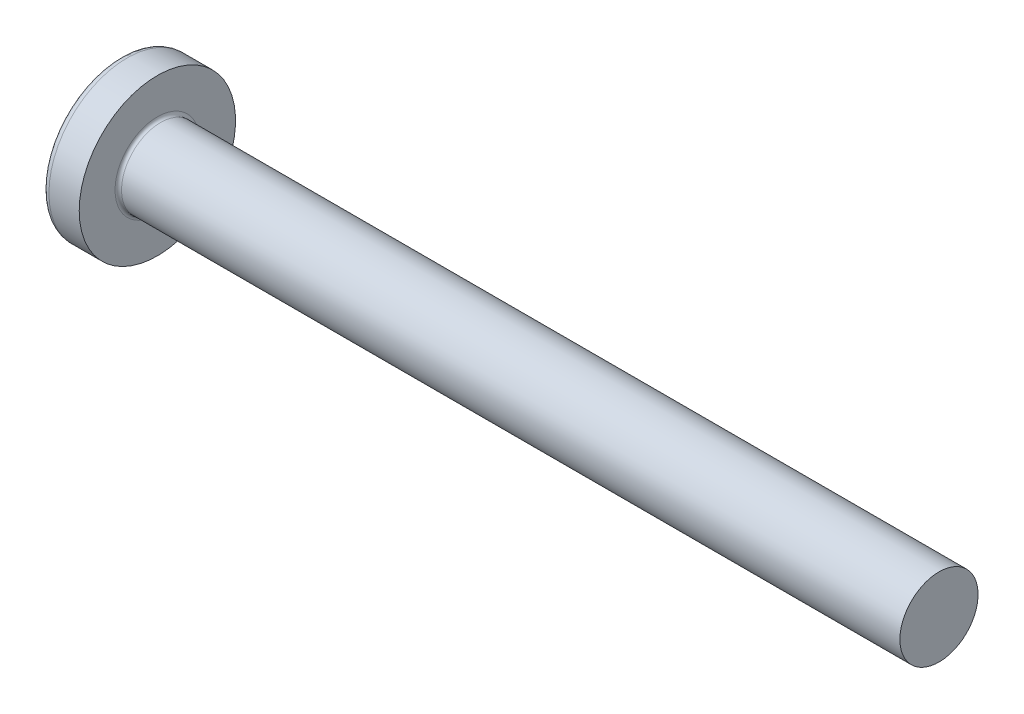
SolidWorks part; units mm, degrees
ref_plane "Plane1" through (0, 0, 0) normal (0, 0, 1) x (1, 0, 0)
ref_plane "Plane2" through (0, 0, 0) normal (0, 1, 0) x (1, 0, 0)
ref_plane "Plane3" through (0, 0, 0) normal (1, 0, 0) x (0, 0, -1)
sketch "BodySke" plane through (0, 0, 0) normal (0, 0, 1) x (1, 0, 0)
  line L0 (4.6, 3) -> (4.6, 6)
  line L1 (5.1, 6.35) -> (5.1, -3.175) construction
  line L2 (-25.4, 0) -> (127, 0) construction
  line L3 (64.6, 0) -> (0, 0)
  line L4 (4.6, 3) -> (64.6, 3)
  line L5 (64.6, 3) -> (64.6, 0)
  line L6 (2.2747, 6) -> (4.6, 6)
  line L8 (26.6, 6.35) -> (26.6, -3.175) construction
  arc A0 (1.8337, 5.7717) -> (0, 0) centre (10, 0) ccw
  arc A2 (1.8337, 5.7717) -> (2.2747, 6) centre (2.2747, 5.46) cw
  dimension "Head_crown_rad" = 10
  dimension "Head_fillet_rad" = 0.54
  dimension "Length" = 60
  dimension "Head_ht" = 4.6
  dimension "Head_dia" = 12
  dimension "Advance" = 1
  dimension "Thread_nom" = 38
  dimension "Diameter" = 6
revolve "Base-Revolve" add sketch "BodySke"
cosmetic thread "ThreadCosmetic" [suppressed]
fillet "Fillet1" radius 0.25 1 edges at (4.6, 0, 3)
sketch "Sketch3" plane through (0, 0, 0) normal (1, 0, 0) x (0, 0, -1)
  line L0 (0.71, -3.35) -> (-0.71, -3.35)
  line L1 (0.71, -3.35) -> (0.71, 3.35)
  line L2 (-0.71, 3.35) -> (0.71, 3.35)
  line L3 (-0.71, 3.35) -> (-0.71, -3.35)
  dimension "Cross_dia" = 6.7
  dimension "D1" = 3.35
  dimension "Cross_width" = 1.42
  dimension "D2" = 0.71
ref_plane "Plane4" through (3.46, 0, 0) normal (1, 0, 0) x (0, 0, -1)
sketch "Sketch4" plane through (3.46, 0, 0) normal (1, 0, 0) x (0, 0, -1)
  line L0 (0.71, -1.6249) -> (-0.71, -1.6249)
  line L1 (0.71, -1.6249) -> (0.71, 1.6249)
  line L2 (-0.71, 1.6249) -> (0.71, 1.6249)
  line L3 (-0.71, 1.6249) -> (-0.71, -1.6249)
  dimension "D1" = 1.42
  dimension "D2" = 3.2498
  dimension "D3" = 0.71
  dimension "D4" = 1.6249
loft "Recess" cut profiles "Sketch3", "Sketch4"
pattern_circular "RecPat" count 2 every 90 about axis through (0, 0, 0) along (1, 0, 0) of "Recess"
sketch "RecCorSke" plane through (0, 0, 0) normal (0, 0, 1) x (1, 0, 0)
  line L0 (-3.175, 0) -> (15.875, 0) construction
  line L1 (-25.4, 0) -> (127, 0) construction
  line L2 (0, 0) -> (0, 1.5224)
  line L3 (0, 1.5224) -> (3.46, 1.2805)
  line L4 (3.46, 1.2805) -> (3.8761, 0)
  line L5 (3.8761, 0) -> (0, 0)
  dimension "Diameter" = 2.561
  dimension "Depth" = 3.46
  dimension "Draft_angle" = 4
  dimension "Bottom_angle" = 18
revolve "RecessCore" cut sketch "RecCorSke" angle 360 about L0
sketch "ThdSchSke" plane through (0, 0, 0) normal (0, 0, 1) x (1, 0, 0)
  line L0 (26.6, -2.4455) -> (26.2117, -3)
  line L1 (26.6, -2.4455) -> (26.9883, -3)
  line L2 (26.9883, -3) -> (26.9883, -3.75)
  line L3 (-3.175, 0) -> (5.1513, 0) construction
  line L5 (26.9883, -3.75) -> (26.2117, -3.75)
  line L6 (26.2117, -3.75) -> (26.2117, -3)
  dimension "Diameter" = 6
  dimension "SideAngle" = 55
  dimension "VeeAngle" = 70
  dimension "Thread_minor" = 4.891
  dimension "Overcut" = 7.5
  dimension "Start" = 26.6
revolve "ThreadSchematic" [suppressed] cut sketch "ThdSchSke" angle 360 about L3
pattern_linear "ThdSchPat" [suppressed]
equation "\"D1@Sketch3\" = \"Cross_dia@Sketch3\" / 2"
equation "\"D2@Sketch3\" = \"Cross_width@Sketch3\" / 2"
equation "\"Depth@RecCorSke\" = \"Cross_depth@Plane4\""
equation "\"D1@Sketch4\" = \"Cross_width@Sketch3\""
equation "\"D2@Sketch4\" = \"Cross_dia@Sketch3\" - 2.0 * \"Cross_depth@Plane4\" * tan(26.5  * 0.017453292)"
equation "\"D3@Sketch4\" = \"D1@Sketch4\" / 2"
equation "\"D4@Sketch4\" = \"D2@Sketch4\" / 2"
equation "\"Thread_length@ThreadCosmetic\" = ((sgn( (\"Length@BodySke\" - \"Advance@BodySke\" * 2.0 ) - \"Thread_nom@BodySke\" )-1)*( (\"Length@BodySke\" - \"Advance@BodySke\" * 2.0 ) - \"Thread_nom@BodySke\" ))/-2+ \"Thread_nom@BodySke\""
equation "\"Thread_minor@ThdSchSke\" = \"Thread_minor@ThreadCosmetic\""
equation "\"Diameter@ThdSchSke\" = \"Diameter@BodySke\""
equation "\"Overcut@ThdSchSke\" = \"Diameter@BodySke\" * 1.25"
equation "\"Start@ThdSchSke\" = \"Head_ht@BodySke\" + \"Length@BodySke\" - \"Thread_length@ThreadCosmetic\"  '---Non-countersunk---"
equation "\"Num_threads@ThdSchPat\" = int( \"Thread_length@ThreadCosmetic\" / \"Advance@BodySke\" + 0.999 )  + 1"
equation "\"Advance@ThdSchPat\" = \"Thread_length@ThreadCosmetic\" /  (\"Num_threads@ThdSchPat\" - 1) 'relax it"
